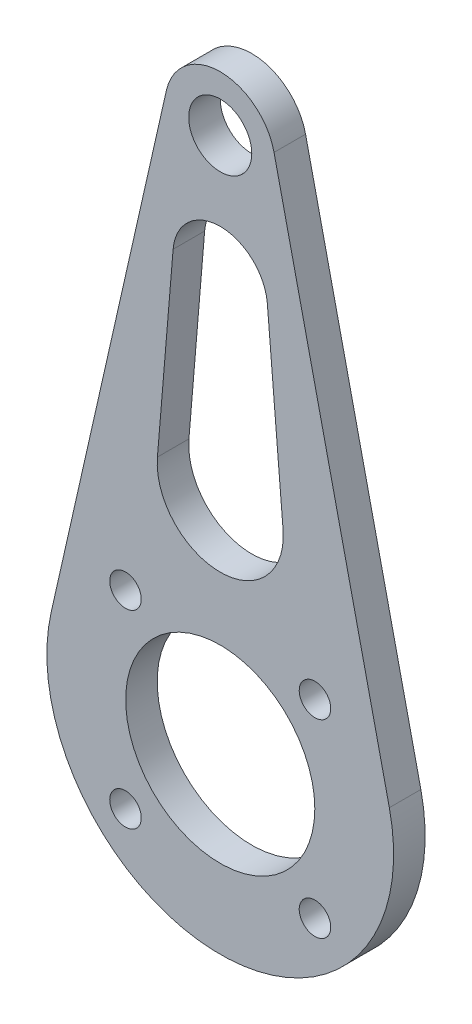
SolidWorks part; units mm, degrees
ref_plane "前视基准面" through (0, 0, 0) normal (0, 0, 1) x (1, 0, 0)
ref_plane "上视基准面" through (0, 0, 0) normal (0, 1, 0) x (1, 0, 0)
ref_plane "右视基准面" through (0, 0, 0) normal (1, 0, 0) x (0, 0, -1)
sketch "草图1" plane through (0, 0, 0) normal (0, 0, 1) x (1, 0, 0)
  line L0 (-3.9187, 21.1434) -> (-11.234, -11.2022)
  line L1 (2.9089, 21.1434) -> (10.2241, -11.2022)
  line L2 (-3.4945, 12.6213) -> (-4.491, 0.7046)
  line L3 (2.4846, 12.6213) -> (3.4812, 0.7046)
  circle A0 centre (-0.5049, -13.6287) radius 6
  arc A1 (2.9089, 21.1434) -> (-3.9187, 21.1434) centre (-0.5049, 20.3713) ccw
  arc A2 (2.4846, 12.6213) -> (-3.4945, 12.6213) centre (-0.5049, 12.3713) ccw
  arc A3 (-4.491, 0.7046) -> (3.4812, 0.7046) centre (-0.5049, 0.3713) ccw
  circle A4 centre (-0.5049, 20.3713) radius 2
  arc A5 (-11.234, -11.2022) -> (10.2241, -11.2022) centre (-0.5049, -13.6287) ccw
  dimension "D1" = 12
  dimension "D2" = 7
  dimension "D4" = 4
  dimension "D5" = 8
  dimension "D7" = 22
  dimension "D9" = 3
  dimension "D3" = 34
  dimension "D6" = 14
  dimension "D8" = 26
extrude "凸台-拉伸1" add sketch "草图1" along normal blind 2
sketch "草图2" plane through (0, 0, 2) normal (0, 0, 1) x (1, 0, 0)
  line L0 (-0.5049, -13.6287) -> (5.5055, -19.6391) construction
  line L1 (0, -1.1) -> (0, 1.1) construction
  circle A0 centre (5.5055, -19.6391) radius 1
  dimension "D2" = 2
  dimension "D1" = 45
  dimension "D3" = 8.5
extrude "切除-拉伸2" cut sketch "草图2" against normal through all
pattern_circular "阵列(圆周)1" count 4 over 360 about axis through (-0.5049, -13.6287, 0) along (0, 0, 1) of "切除-拉伸2"
